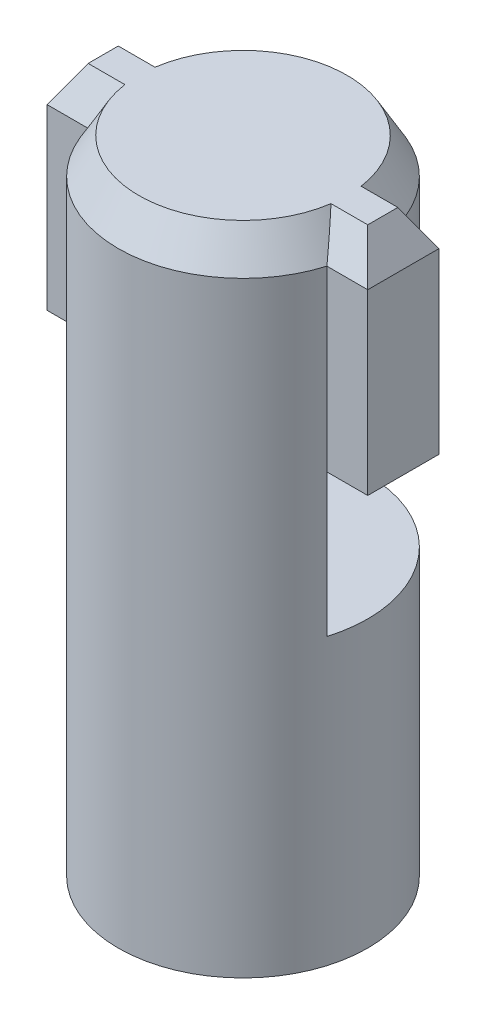
SolidWorks part; units mm, degrees
ref_plane "Спереди" through (0, 0, 0) normal (0, 0, 1) x (1, 0, 0)
ref_plane "Сверху" through (0, 0, 0) normal (0, 1, 0) x (1, 0, 0)
ref_plane "Справа" through (0, 0, 0) normal (1, 0, 0) x (0, 0, -1)
sketch "Sketch1" plane through (0, 0, 0) normal (0, 1, 0) x (1, 0, 0)
  circle A0 centre (0, 0) radius 3.5
  dimension "D1" = 7
extrude "Boss-Extrude1" add sketch "Sketch1" along normal blind 18
sketch "Sketch2" plane through (0, 18, 0) normal (0, 1, 0) x (1, 0, 0)
  line L1 (4.5, 1) -> (-4.5, 1)
  line L2 (4.5, 1) -> (4.5, -1)
  line L3 (4.5, -1) -> (-4.5, -1)
  line L4 (-4.5, 1) -> (-4.5, -1)
  line L5 (4.5, 1) -> (-4.5, -1) construction
  line L6 (4.5, -1) -> (-4.5, 1) construction
  point P0 (0, 0)
  dimension "D1" = 2
  dimension "D2" = 9
extrude "Boss-Extrude3" add sketch "Sketch2" against normal blind 10
sketch "Sketch3" plane through (0, 0, 0) normal (0, -1, 0) x (1, 0, 0)
  line L0 (3.3541, 1) -> (-3.3541, 1) construction
  line L1 (-3.5, 0) -> (3.5, 0) construction
  line L3 (-5, 1) -> (5, 1)
  line L4 (-5, 1) -> (-5, -3.5)
  line L5 (-5, -3.5) -> (5, -3.5)
  line L6 (5, 1) -> (5, -3.5)
  line L7 (-5, 1) -> (5, -3.5) construction
  line L8 (-5, -3.5) -> (5, 1) construction
  circle A0 centre (0, 0) radius 3.5 construction
  point P7 (0, -1.25)
  point P12 (0, 1)
  point P13 (0, 1)
  point P16 (0, -3.5)
  dimension "D1" = 2
  dimension "D2" = 10
extrude "Cut-Extrude3" cut sketch "Sketch3" against normal blind 4 from offset 8 offset against normal yes
chamfer "Chamfer1" distance 1 angle 30 8 edges at (-3.9271, 18, 1) (-4.5, 18, 0) (-3.9271, 18, -1) (0, 18, -3.5) (3.9271, 18, -1) (4.5, 18, 0) (3.9271, 18, 1) (0, 18, 3.5)
